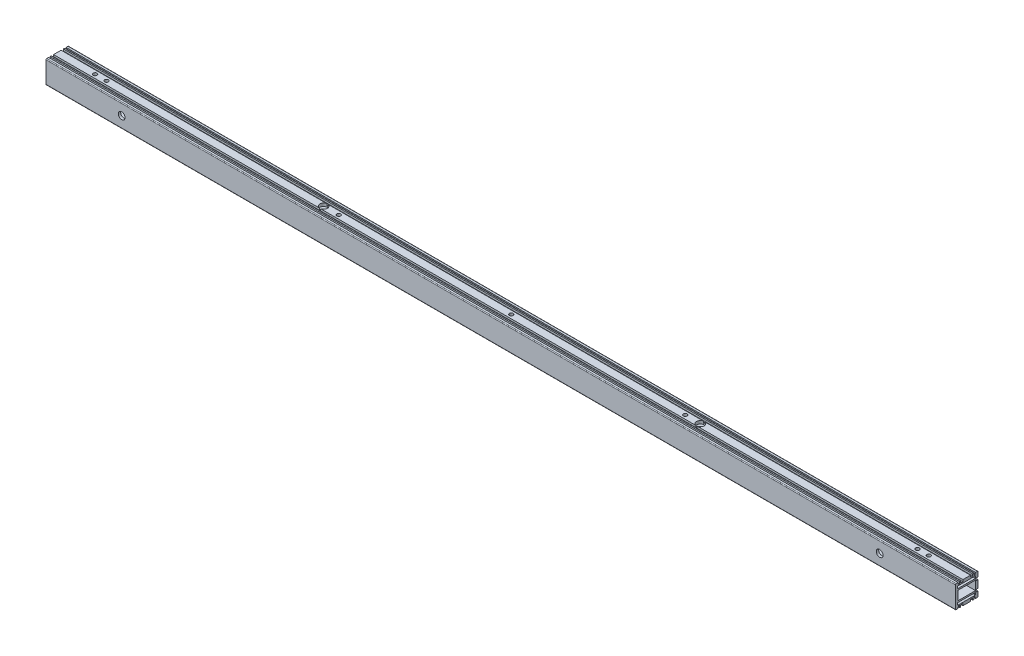
SolidWorks part; units mm, degrees
ref_plane "前视基准面" through (0, 0, 0) normal (0, 0, 1) x (1, 0, 0)
ref_plane "上视基准面" through (0, 0, 0) normal (0, 1, 0) x (1, 0, 0)
ref_plane "右视基准面" through (0, 0, 0) normal (1, 0, 0) x (0, 0, -1)
sketch "草图1" plane through (0, 0, 0) normal (1, 0, 0) x (0, 0, -1)
  line L0 (-15, 15) -> (15, -15) construction
  line L1 (-14, 15) -> (-11.5, 15)
  line L2 (-15, 14) -> (-15, -14)
  line L3 (-14, -15) -> (-11.5, -15)
  line L4 (15, 14) -> (15, 8)
  line L5 (15, 15) -> (-15, -15) construction
  line L6 (-11.5, 15) -> (-11.5, 13.5)
  line L7 (-11.5, 13.5) -> (-11.4, 13.5)
  line L8 (-11, 13.1) -> (-11, 12)
  line L9 (-11, 12) -> (-9.5, 12)
  line L10 (-9.5, 12) -> (-9.5, 15)
  line L11 (-9.5, 15) -> (-8, 15)
  line L12 (-8, 15) -> (-8, 12.5)
  line L13 (-8, 12.5) -> (-5, 12.5)
  line L14 (-5, 12.5) -> (-5, 15)
  line L15 (-5, 15) -> (5, 15)
  line L16 (0, 21.5201) -> (0, -18.309) construction
  line L17 (0, 55) -> (0, -55) construction
  line L18 (5, 12.5) -> (5, 15)
  line L19 (8, 12.5) -> (5, 12.5)
  line L20 (8, 15) -> (8, 12.5)
  line L21 (9.5, 15) -> (8, 15)
  line L22 (9.5, 12) -> (9.5, 15)
  line L23 (11, 12) -> (9.5, 12)
  line L24 (11, 13.1) -> (11, 12)
  line L25 (11.5, 13.5) -> (11.4, 13.5)
  line L26 (11.5, 15) -> (11.5, 13.5)
  line L27 (8, 15) -> (9.5, 15)
  line L28 (11.5, 15) -> (14, 15)
  line L29 (-19.8303, 0) -> (22.13, 0) construction
  line L30 (55, 0) -> (-55, 0) construction
  line L31 (8, -15) -> (9.5, -15)
  line L32 (11.5, -15) -> (11.5, -13.5)
  line L33 (11.5, -13.5) -> (11.4, -13.5)
  line L34 (11, -13.1) -> (11, -12)
  line L35 (11, -12) -> (9.5, -12)
  line L36 (9.5, -12) -> (9.5, -15)
  line L37 (9.5, -15) -> (8, -15)
  line L38 (8, -15) -> (8, -12.5)
  line L39 (8, -12.5) -> (5, -12.5)
  line L40 (5, -12.5) -> (5, -15)
  line L41 (-5, -15) -> (5, -15)
  line L42 (-5, -12.5) -> (-5, -15)
  line L43 (-8, -12.5) -> (-5, -12.5)
  line L44 (-8, -15) -> (-8, -12.5)
  line L45 (-9.5, -15) -> (-8, -15)
  line L46 (-9.5, -12) -> (-9.5, -15)
  line L47 (-11, -12) -> (-9.5, -12)
  line L48 (-11, -13.1) -> (-11, -12)
  line L49 (-11.5, -13.5) -> (-11.4, -13.5)
  line L50 (-11.5, -15) -> (-11.5, -13.5)
  line L51 (-9.5, -15) -> (-8, -15)
  line L52 (-5, -15) -> (5, -15)
  line L53 (8, -15) -> (9.5, -15)
  line L54 (11.5, -15) -> (14, -15)
  line L55 (15, 8) -> (12.5, 8)
  line L56 (12.5, 8) -> (12.5, 5)
  line L57 (12.5, 5) -> (15, 5)
  line L58 (12.5, -5) -> (15, -5)
  line L59 (12.5, -8) -> (12.5, -5)
  line L60 (15, -8) -> (12.5, -8)
  line L61 (15, 5) -> (15, -5)
  line L62 (15, -8) -> (15, -14)
  line L63 (12, -10.5) -> (12, -8.5)
  line L64 (-11.5, 11) -> (11.5, 11)
  line L65 (-12, 10.5) -> (-12, 8.5)
  line L66 (-11.5, 8) -> (11.5, 8)
  line L67 (12, 10.5) -> (12, 8.5)
  line L68 (-11.5, -8) -> (11.5, -8)
  line L69 (-12, -10.5) -> (-12, -8.5)
  line L70 (-11.5, -11) -> (11.5, -11)
  line L72 (-11.75, 6) -> (11.75, 6)
  line L73 (-11.75, 6) -> (-11.75, -6)
  line L74 (-11.75, -6) -> (11.75, -6)
  line L75 (11.75, 6) -> (11.75, -6)
  arc A0 (12, 8.5) -> (11.5, 8) centre (11.5, 8.5) cw
  arc A1 (11.5, 11) -> (12, 10.5) centre (11.5, 10.5) cw
  arc A2 (-11.5, 11) -> (-12, 10.5) centre (-11.5, 10.5) ccw
  arc A3 (-11.5, 8) -> (-12, 8.5) centre (-11.5, 8.5) cw
  arc A4 (-11, -13.1) -> (-11.4, -13.5) centre (-11.4, -13.1) cw
  arc A5 (11.4, -13.5) -> (11, -13.1) centre (11.4, -13.1) cw
  arc A6 (11.4, 13.5) -> (11, 13.1) centre (11.4, 13.1) ccw
  arc A7 (-11, 13.1) -> (-11.4, 13.5) centre (-11.4, 13.1) ccw
  arc A8 (-11.5, -8) -> (-12, -8.5) centre (-11.5, -8.5) ccw
  arc A9 (-11.5, -11) -> (-12, -10.5) centre (-11.5, -10.5) cw
  arc A10 (11.5, -11) -> (12, -10.5) centre (11.5, -10.5) ccw
  arc A11 (12, -8.5) -> (11.5, -8) centre (11.5, -8.5) ccw
  arc A12 (14, 15) -> (15, 14) centre (14, 14) cw
  arc A13 (14, -15) -> (15, -14) centre (14, -14) ccw
  arc A14 (-15, -14) -> (-14, -15) centre (-14, -14) ccw
  arc A15 (-15, 14) -> (-14, 15) centre (-14, 14) cw
  point P69 (12, 11)
  point P72 (-12, 11)
  point P77 (-11, -13.5)
  point P80 (11, -13.5)
  point P83 (11, 13.5)
  point P86 (-11, 13.5)
  point P99 (-12, -11)
  point P100 (12, -11)
  dimension "D17" = 0.5
  dimension "D18" = 0.4
  dimension "D21" = 1
  dimension "D1" = 3.5
  dimension "D2" = 1.5
  dimension "D3" = 0.5
  dimension "D4" = 1.5
  dimension "D5" = 3
  dimension "D6" = 30
  dimension "D7" = 30
  dimension "D8" = 1.5
  dimension "D9" = 2.5
  dimension "D10" = 3
  dimension "D11" = 2.5
  dimension "D12" = 7
  dimension "D13" = 3
  dimension "D14" = 4
  dimension "D15" = 3
  dimension "D16" = 24
  dimension "D19" = 23.5
  dimension "D20" = 12
extrude "凸台-拉伸1" add sketch "草图1" along normal mid plane 1202 contours A15 L2 A14 L3 L50 L49 A4 L48 L47 L46 L45 L44 L43 L42 L41 L40 L39 L38 L31 L36 L35 L34 A5 L33 L32 L54 A13 L62 L60 L59 L58 L61 L57 L56 L55 L4 A12 L28 L26 L25 A6 L24 L23 L22 L21 L20 L19 L18 L15 L14 L13
hole_wizard "M6 螺纹孔1" positions "草图5" profile "草图4" tap size "M6" standard "GB"
sketch "草图5" plane through (0, 0, -15) normal (0, 0, -1) x (-1, 0, 0)
  line L0 (-601, -15) -> (601, -15) construction
  line L1 (-571, 9) -> (-571, -9) construction
  point P0 (-551, 0)
  point P1 (-536, 0)
  point P4 (536, 0)
  point P7 (551, 0)
  dimension "D1" = 15
  dimension "D2" = 20
sketch "草图4" plane through (551, 0, -15) normal (1, 0, 0) x (0, 1, 0)
  line L0 (0, 0) -> (0, 16.5022)
  line L1 (0, 16.5022) -> (2.5, 15)
  line L2 (2.5, 15) -> (2.5, 0)
  line L5 (2.5, 0) -> (0, 0)
  line L10 (0, 16.5022) -> (-2.5, 15) construction
  line L11 (0, -6.35) -> (0, 107.95) construction
  dimension "螺纹孔钻头直径" = 5
  dimension "螺纹孔钻头深度" = 15
  dimension "导头角度" = 118
cosmetic thread "孔螺蚊线1" parameters "D1"=3.25, "D2"=6
cosmetic thread "孔螺蚊线2" parameters "D1"=3.25, "D2"=6
cosmetic thread "孔螺蚊线3" parameters "D1"=3.25, "D2"=6
cosmetic thread "孔螺蚊线4" parameters "D1"=3.25, "D2"=6
hole_wizard "M6 螺纹孔2" positions "草图7" profile "草图6" tap size "M6" standard "GB"
sketch "草图7" plane through (0, 15, 0) normal (0, 1, 0) x (-1, 0, 0)
  line L0 (571, 5) -> (571, -5) construction
  line L1 (-601, 15) -> (601, 15) construction
  point P0 (551, 0)
  point P1 (536, 0)
  point P4 (-536, 0)
  point P7 (-551, 0)
  dimension "D1" = 20
  dimension "D2" = 15
sketch "草图6" plane through (-551, 15, 0) normal (1, 0, 0) x (0, 0, 1)
  line L0 (0, 0) -> (0, 16.5022)
  line L1 (0, 16.5022) -> (2.5, 15)
  line L2 (2.5, 15) -> (2.5, 0)
  line L5 (2.5, 0) -> (0, 0)
  line L10 (0, 16.5022) -> (-2.5, 15) construction
  line L11 (0, -6.35) -> (0, 107.95) construction
  dimension "螺纹孔钻头直径" = 5
  dimension "螺纹孔钻头深度" = 15
  dimension "导头角度" = 118
cosmetic thread "孔螺蚊线5" parameters "D1"=9, "D2"=6
cosmetic thread "孔螺蚊线6" parameters "D1"=9, "D2"=6
cosmetic thread "孔螺蚊线7" parameters "D1"=9, "D2"=6
cosmetic thread "孔螺蚊线8" parameters "D1"=9, "D2"=6
sketch "草图8" plane through (0, 0, 15) normal (0, 0, 1) x (1, 0, 0)
  line L0 (-601, 0) -> (601, 0) construction
  line L1 (-601, 14) -> (-601, -14) construction
  line L2 (601, 14) -> (601, -14) construction
  circle A0 centre (-501, 0) radius 4.5
  circle A1 centre (501, 0) radius 4.5
  dimension "D3" = 9
  dimension "D1" = 100
  dimension "D2" = 100
extrude "切除-拉伸1" cut sketch "草图8" against normal through all
sketch "草图10" plane through (0, 15, 0) normal (0, 1, 0) x (-1, 0, 0)
  line L0 (601, 0) -> (-601, 0) construction
  line L1 (601, 5) -> (601, -5) construction
  line L2 (-601, 5) -> (-601, -5) construction
  circle A0 centre (249, 0) radius 5.05
  circle A1 centre (-249, 0) radius 5.05
  dimension "D3" = 10.1
  dimension "D1" = 352
  dimension "D2" = 352
hole_wizard "M6 螺纹孔3" positions "草图12" profile "草图11" tap size "M6" standard "GB"
sketch "草图12" plane through (0, 15, 0) normal (0, 1, 0) x (-1, 0, 0)
  line L0 (-601, 15) -> (601, 15) construction
  line L1 (601, 5) -> (601, -5) construction
  line L2 (-601, 5) -> (-601, -5) construction
  point P0 (229, 0)
  point P1 (1, 0)
  point P3 (-229, 0)
  dimension "D1" = 15
  dimension "D2" = 372
  dimension "D3" = 15
  dimension "D4" = 602
  dimension "D5" = 15
  dimension "D6" = 372
sketch "草图11" plane through (-229, 15, 0) normal (1, 0, 0) x (0, 0, 1)
  line L0 (0, 0) -> (0, 16.5022)
  line L1 (0, 16.5022) -> (2.5, 15)
  line L2 (2.5, 15) -> (2.5, 0)
  line L5 (2.5, 0) -> (0, 0)
  line L10 (0, 16.5022) -> (-2.5, 15) construction
  line L11 (0, -6.35) -> (0, 107.95) construction
  dimension "螺纹孔钻头直径" = 5
  dimension "螺纹孔钻头深度" = 15
  dimension "导头角度" = 118
cosmetic thread "孔螺蚊线9" parameters "D1"=9, "D2"=6
cosmetic thread "孔螺蚊线10" parameters "D1"=9, "D2"=6
cosmetic thread "孔螺蚊线11" parameters "D1"=9, "D2"=6
extrude "切除-拉伸15" cut sketch "草图10" against normal through all
sketch "草图13" plane through (0, -15, 0) normal (0, -1, 0) x (1, 0, 0)
  circle A0 centre (229, 0) radius 4.5
  circle A1 centre (-1, 0) radius 4.5
  circle A2 centre (-229, 0) radius 4.5
  dimension "D1" = 9
extrude "切除-拉伸16" cut sketch "草图13" against normal blind 15
hole_wizard "M6 螺纹孔4" positions "草图15" profile "草图14" tap size "M6" standard "GB"
sketch "草图15" plane through (0, 0, -15) normal (0, 0, -1) x (-1, 0, 0)
  line L0 (-601, -8) -> (-601, -14) construction
  line L1 (-601, -15) -> (-249.7089, -15) construction
  line L2 (601, 5) -> (601, -5) construction
  point P0 (341, 0)
  point P1 (281, 0)
  point P3 (-281, 0)
  point P5 (-341, 0)
  dimension "D1" = 60
  dimension "D2" = 260
  dimension "D3" = 15
  dimension "D4" = 260
  dimension "D5" = 60
sketch "草图14" plane through (-341, 0, -15) normal (1, 0, 0) x (0, 1, 0)
  line L0 (0, 0) -> (0, 16.5022)
  line L1 (0, 16.5022) -> (2.5, 15)
  line L2 (2.5, 15) -> (2.5, 0)
  line L5 (2.5, 0) -> (0, 0)
  line L10 (0, 16.5022) -> (-2.5, 15) construction
  line L11 (0, -6.35) -> (0, 107.95) construction
  dimension "螺纹孔钻头直径" = 5
  dimension "螺纹孔钻头深度" = 15
  dimension "导头角度" = 118
cosmetic thread "孔螺蚊线12" parameters "D1"=3.25, "D2"=6
cosmetic thread "孔螺蚊线13" parameters "D1"=3.25, "D2"=6
cosmetic thread "孔螺蚊线14" parameters "D1"=3.25, "D2"=6
cosmetic thread "孔螺蚊线15" parameters "D1"=3.25, "D2"=6
hole_wizard "M6 螺纹孔5" positions "草图17" profile "草图16" tap size "M6" standard "GB"
sketch "草图17" plane through (0, 0, -15) normal (0, 0, -1) x (-1, 0, 0)
  line L0 (249.7089, -15) -> (601, -15) construction
  line L1 (601, 5) -> (601, -5) construction
  point P0 (446, 0)
  point P1 (376, 0)
  dimension "D1" = 15
  dimension "D2" = 15
  dimension "D3" = 70
  dimension "D4" = 155
sketch "草图16" plane through (-446, 0, -15) normal (1, 0, 0) x (0, 1, 0)
  line L0 (0, 0) -> (0, 16.5022)
  line L1 (0, 16.5022) -> (2.5, 15)
  line L2 (2.5, 15) -> (2.5, 0)
  line L5 (2.5, 0) -> (0, 0)
  line L10 (0, 16.5022) -> (-2.5, 15) construction
  line L11 (0, -6.35) -> (0, 107.95) construction
  dimension "螺纹孔钻头直径" = 5
  dimension "螺纹孔钻头深度" = 15
  dimension "导头角度" = 118
cosmetic thread "孔螺蚊线16" parameters "D1"=3.25, "D2"=6
cosmetic thread "孔螺蚊线21" parameters "D1"=3.25, "D2"=6
